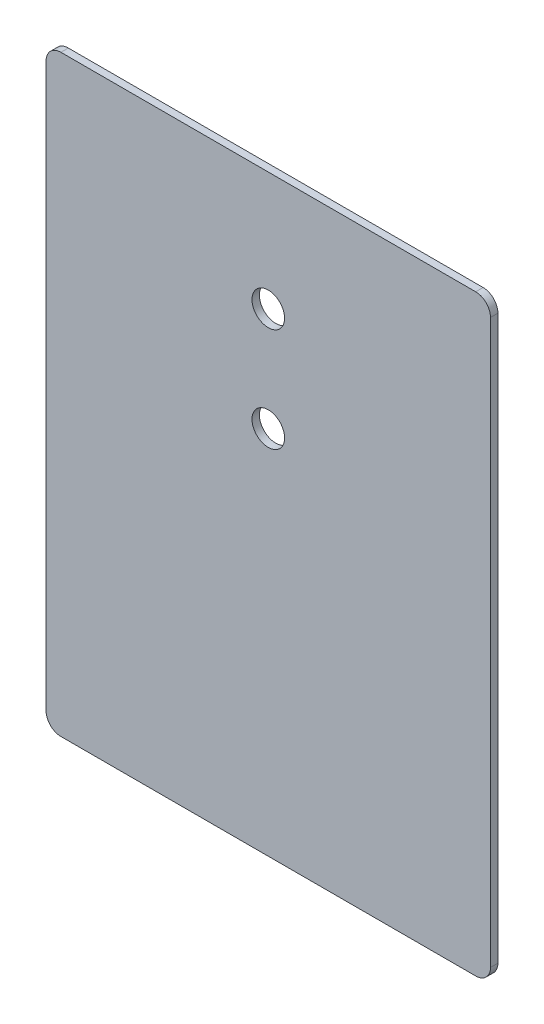
SolidWorks part; units mm, degrees
ref_plane "前视基准面" through (0, 0, 0) normal (0, 0, 1) x (1, 0, 0)
ref_plane "上视基准面" through (0, 0, 0) normal (0, 1, 0) x (1, 0, 0)
ref_plane "右视基准面" through (0, 0, 0) normal (1, 0, 0) x (0, 0, -1)
sketch "草图1" plane through (0, 0, 0) normal (0, 0, 1) x (1, 0, 0)
  line L1 (-188.8889, 284.0444) -> (111.1111, 284.0444)
  line L2 (-188.8889, 284.0444) -> (-188.8889, -115.9556)
  line L3 (-188.8889, -115.9556) -> (111.1111, -115.9556)
  line L4 (111.1111, 284.0444) -> (111.1111, -115.9556)
  dimension "D1" = 300
  dimension "D2" = 400
extrude "凸台-拉伸1" add sketch "草图1" along normal blind 5 contours L1 L4 L3 L2
fillet "圆角1" radius 10 4 edges at (111.1111, -115.9556, 2.5) (-188.8889, -115.9556, 2.5) (-188.8889, 284.0444, 2.5) (111.1111, 284.0444, 2.5)
sketch "草图2" plane through (0, 0, 0) normal (0, 0, 1) x (1, 0, 0)
  line L0 (-38.8889, 284.0444) -> (-38.8889, -115.9556) construction
  line L1 (-178.8889, 284.0444) -> (101.1111, 284.0444) construction
  line L2 (-178.8889, -115.9556) -> (101.1111, -115.9556) construction
  circle A0 centre (-38.8889, 204.0444) radius 11
  circle A1 centre (-38.8889, 134.0444) radius 11
  point P10 (0, 0)
  dimension "D1" = 80
  dimension "D2" = 150
extrude "切除-拉伸3" cut sketch "草图2" along normal blind 5
